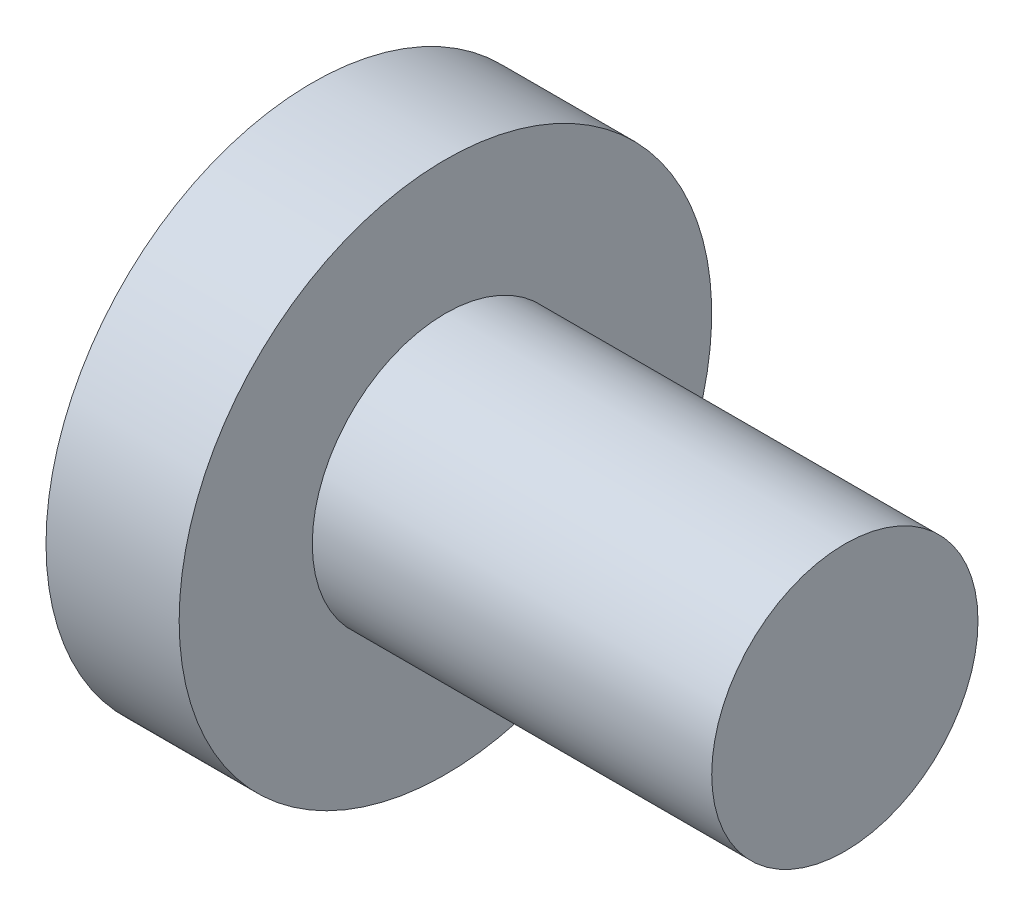
SolidWorks part; units mm, degrees
ref_plane "Front Plane" through (0, 0, 0) normal (0, 0, 1) x (1, 0, 0)
ref_plane "Top Plane" through (0, 0, 0) normal (0, 1, 0) x (1, 0, 0)
ref_plane "Right Plane" through (0, 0, 0) normal (1, 0, 0) x (0, 0, -1)
sketch "Sketch1" plane through (0, 0, 0) normal (0, 1, 0) x (1, 0, 0)
  line L1 (-1.6781, -0.0194) -> (13.3219, -0.0194)
  line L3 (-4.38, -5.0194) -> (13.3219, -5.0194)
  line L4 (13.3219, -0.0194) -> (13.3219, -5.0194)
  line L5 (-6.6781, 4.9806) -> (-1.6781, 4.9806)
  line L6 (-6.6781, 4.9806) -> (-6.6781, -5.0194)
  line L7 (-6.6781, -5.0194) -> (-4.38, -5.0194)
  line L8 (-1.6781, 4.9806) -> (-1.6781, -0.0194)
  dimension "D1" = 10
  dimension "D2" = 5
  dimension "D3" = 5
  dimension "D4" = 15
revolve "Revolve1" add sketch "Sketch1" angle 360 about L3
